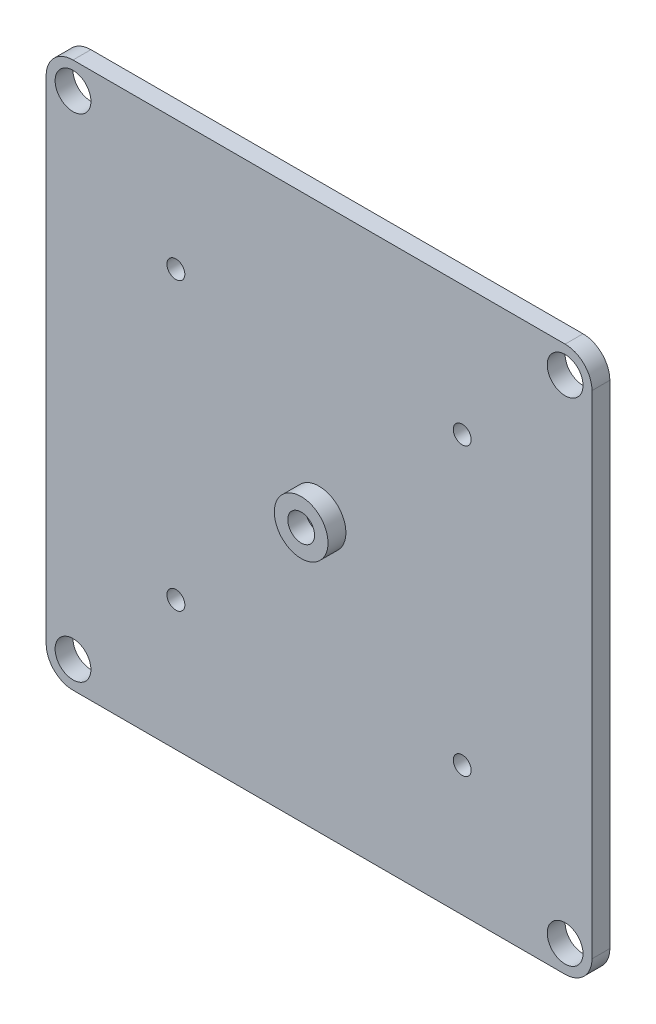
SolidWorks part; units mm, degrees
ref_plane "Plan de face" through (0, 0, 0) normal (0, 0, 1) x (1, 0, 0)
ref_plane "Plan de dessus" through (0, 0, 0) normal (0, 1, 0) x (1, 0, 0)
ref_plane "Plan de droite" through (0, 0, 0) normal (1, 0, 0) x (0, 0, -1)
sketch "Esquisse1" plane through (0, 0, 0) normal (0, 0, 1) x (1, 0, 0)
  line L1 (-152.5, -152.5) -> (152.5, -152.5)
  line L2 (-152.5, -152.5) -> (-152.5, 152.5)
  line L3 (-152.5, 152.5) -> (152.5, 152.5)
  line L4 (152.5, -152.5) -> (152.5, 152.5)
  dimension "D1" = 152.5
  dimension "D2" = 305
  dimension "D3" = 305
  dimension "D4" = 152.5
extrude "Boss.-Extru.1" add sketch "Esquisse1" along normal blind 10
sketch "Esquisse2" plane through (0, 0, 10) normal (0, 0, 1) x (1, 0, 0)
  line L0 (152.5, 152.5) -> (-152.5, 152.5) construction
  line L1 (152.5, -152.5) -> (152.5, 152.5) construction
  line L2 (-152.5, 152.5) -> (-152.5, -152.5) construction
  line L3 (-152.5, -152.5) -> (152.5, -152.5) construction
  circle A0 centre (137.5, 137.5) radius 15 construction
  circle A1 centre (137.5, -137.5) radius 15 construction
  circle A2 centre (-137.5, -137.5) radius 15 construction
  circle A3 centre (-137.5, 137.5) radius 15 construction
  circle A4 centre (137.5, 137.5) radius 10
  circle A5 centre (137.5, -137.5) radius 10
  circle A6 centre (-137.5, -137.5) radius 10
  circle A7 centre (-137.5, 137.5) radius 10
  dimension "D1" = 30
  dimension "3" = 30
  dimension "D2" = 30
  dimension "D3" = 30
  dimension "D4" = 20
  dimension "D5" = 20
  dimension "D6" = 20
  dimension "D7" = 20
extrude "Enlèv. mat.-Extru.10" cut sketch "Esquisse2" against normal blind 10
fillet "Congé2" radius 15 4 edges at (152.5, 152.5, 5) (152.5, -152.5, 5) (-152.5, -152.5, 5) (-152.5, 152.5, 5)
sketch "Esquisse3" plane through (0, 0, 10) normal (0, 0, 1) x (1, 0, 0)
  line L1 (-100, -100) -> (100, -100) construction
  line L2 (-100, -100) -> (-100, 100) construction
  line L3 (-100, 100) -> (100, 100) construction
  line L4 (100, -100) -> (100, 100) construction
  line L5 (-80, -80) -> (80, -80) construction
  line L6 (-80, -80) -> (-80, 80) construction
  line L7 (-80, 80) -> (80, 80) construction
  line L8 (80, -80) -> (80, 80) construction
  circle A0 centre (80, 80) radius 5
  circle A1 centre (80, -80) radius 5
  circle A2 centre (-80, -80) radius 5
  circle A3 centre (-80, 80) radius 5
  point P4 (0, 0)
  dimension "D9" = 10
  dimension "D10" = 10
  dimension "D11" = 10
  dimension "D12" = 10
  dimension "D1" = 200
  dimension "D2" = 200
  dimension "D3" = 100
  dimension "D4" = 100
  dimension "D5" = 20
  dimension "D6" = 20
  dimension "D7" = 20
  dimension "D8" = 20
extrude "Enlèv. mat.-Extru.11" cut sketch "Esquisse3" against normal blind 10
sketch "Esquisse4" plane through (0, 0, 10) normal (0, 0, 1) x (1, 0, 0)
  circle A0 centre (0, 0) radius 15
  dimension "D1" = 30
extrude "Boss.-Extru.2" add sketch "Esquisse4" along normal blind 10
sketch "Esquisse5" plane through (0, 0, 20) normal (0, 0, 1) x (1, 0, 0)
  circle A0 centre (0, 0) radius 7.5
  dimension "D1" = 15
extrude "Enlèv. mat.-Extru.12" cut sketch "Esquisse5" against normal blind 10
